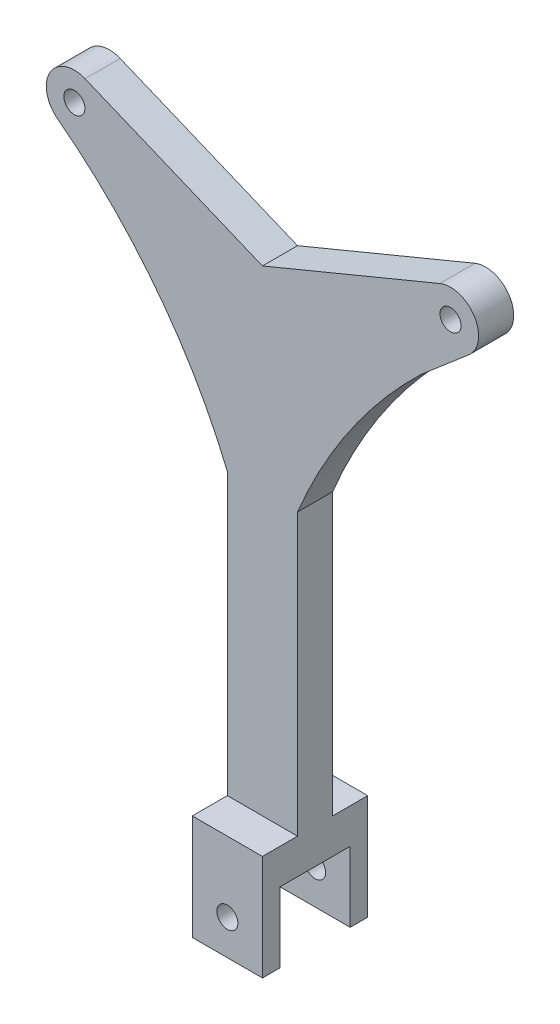
SolidWorks part; units mm, degrees
material "PUR"
ref_plane "Ön Düzlem" through (0, 0, 0) normal (0, 0, 1) x (1, 0, 0)
ref_plane "Üst Düzlem" through (0, 0, 0) normal (0, 1, 0) x (1, 0, 0)
ref_plane "Sağ Düzlem" through (0, 0, 0) normal (1, 0, 0) x (0, 0, -1)
sketch "Çizim1" plane through (0, 0, 0) normal (0, 0, 1) x (1, 0, 0)
  line L0 (0, 12.9383) -> (0, -32.1776) construction
  line L1 (-26.7925, 11.0978) -> (17.8667, -7.4006) construction
  line L2 (-18.9711, -7.8581) -> (26.7925, 11.0978) construction
  line L3 (29.3923, 8.0579) -> (22.6601, 2.3005)
  line L5 (1.5307, -3.6955) -> (9.973, -0.1986)
  line L7 (-25.2618, 14.7933) -> (0, 4.3296)
  line L9 (25.2618, 14.7933) -> (0, 4.3296)
  line L12 (6.6568, -0.1986) -> (-3.9951, -0.1986)
  line L17 (-5, -63.5249) -> (5, -63.5249)
  line L19 (3.9951, -0.1986) -> (9.973, -0.1986)
  line L20 (6.6568, -0.1986) -> (-1.5307, -3.6955)
  line L21 (-5, -63.5249) -> (-5, -23.5249)
  line L23 (5, -63.5249) -> (5, -23.5249)
  arc A0 (-25.2618, 14.7933) -> (-29.0768, 7.8142) centre (-26.7925, 11.0978) ccw
  arc A1 (29.3923, 8.0579) -> (25.2618, 14.7933) centre (26.7925, 11.0978) ccw
  arc A2 (-3.9951, -0.1986) -> (-1.5307, -3.6955) centre (0, 0) ccw
  arc A3 (-29.3563, 8.0275) -> (-5, -23.5249) centre (-75.5569, -52.8131) cw
  arc A4 (22.6601, 2.3005) -> (5, -23.5249) centre (75.5538, -52.8206) ccw
  arc A5 (1.5307, -3.6955) -> (3.9951, -0.1986) centre (0, 0) ccw
  point P17 (0, -38.5249)
  point P19 (0, -20)
  dimension "D2" = 67.5
  dimension "D3" = 8
  dimension "D4" = 29
  dimension "D1" = 67.5
  dimension "D5" = 10
  dimension "D6" = 20
  dimension "D7" = 29
  dimension "D8" = 40
extrude "Yükseklik-Ekstrüzyon1" add sketch "Çizim1" along normal mid plane 5
sketch "Çizim2" plane through (0, 0, 2.5) normal (0, 0, 1) x (1, 0, 0)
  circle A0 centre (-26.7925, 11.0978) radius 1.5
  circle A1 centre (26.7925, 11.0978) radius 1.5
  dimension "D1" = 3
extrude "Kes-Ekstrüzyon1" cut sketch "Çizim2" against normal mid plane 22
sketch "Çizim3" plane through (0, -63.5249, 0) normal (0, -1, 0) x (1, 0, 0)
  line L1 (-5, 7.5) -> (5, 7.5)
  line L2 (-5, 7.5) -> (-5, -7.5)
  line L3 (-5, -7.5) -> (5, -7.5)
  line L4 (5, 7.5) -> (5, -7.5)
  line L5 (-5, 7.5) -> (5, -7.5) construction
  line L6 (-5, -7.5) -> (5, 7.5) construction
  point P0 (0, 0)
  dimension "D1" = 10
  dimension "D2" = 15
extrude "Yükseklik-Ekstrüzyon2" add sketch "Çizim3" along normal blind 15
sketch "Çizim4" plane through (0, -78.5249, 0) normal (0, -1, 0) x (1, 0, 0)
  line L0 (5, 2.5) -> (5, -2.5) construction
  line L1 (-5, 5) -> (5, 5)
  line L2 (-5, 5) -> (-5, -5)
  line L3 (-5, -5) -> (5, -5)
  line L4 (5, 5) -> (5, -5)
  line L5 (-5, 5) -> (5, -5) construction
  line L6 (-5, -5) -> (5, 5) construction
  point P0 (0, 0)
  dimension "D1" = 10
  dimension "D2" = 10
extrude "Kes-Ekstrüzyon2" cut sketch "Çizim4" against normal blind 10
sketch "Çizim5" plane through (0, 0, 7.5) normal (0, 0, 1) x (1, 0, 0)
  line L0 (5, -78.5249) -> (-5, -78.5249) construction
  line L1 (5, -78.5249) -> (5, -63.5249) construction
  circle A0 centre (0, -73.5249) radius 1.5
  dimension "D1" = 3
  dimension "D2" = 5
  dimension "D3" = 5
extrude "Kes-Ekstrüzyon3" cut sketch "Çizim5" against normal blind 18
